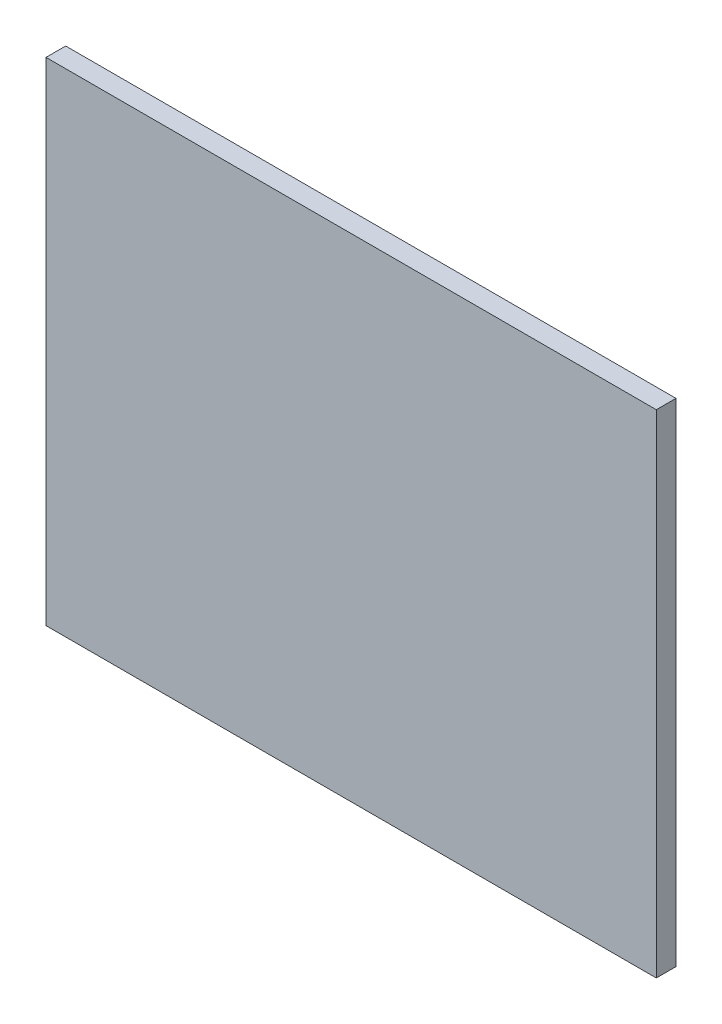
SolidWorks part; units mm, degrees
ref_plane "前视基准面" through (0, 0, 0) normal (0, 0, 1) x (1, 0, 0)
ref_plane "上视基准面" through (0, 0, 0) normal (0, 1, 0) x (1, 0, 0)
ref_plane "右视基准面" through (0, 0, 0) normal (1, 0, 0) x (0, 0, -1)
sketch "草图1" plane through (0, 0, 0) normal (0, 0, 1) x (1, 0, 0)
  line L1 (0, 0) -> (155, 0)
  line L2 (0, 0) -> (0, 125)
  line L3 (0, 125) -> (155, 125)
  line L4 (155, 0) -> (155, 125)
  line L5 (0, 0) -> (155, 125) construction
  line L6 (0, 125) -> (155, 0) construction
  point P4 (77.5, 62.5)
  dimension "D1" = 155
  dimension "D2" = 125
extrude "凸台-拉伸1" add sketch "草图1" along normal blind 5
